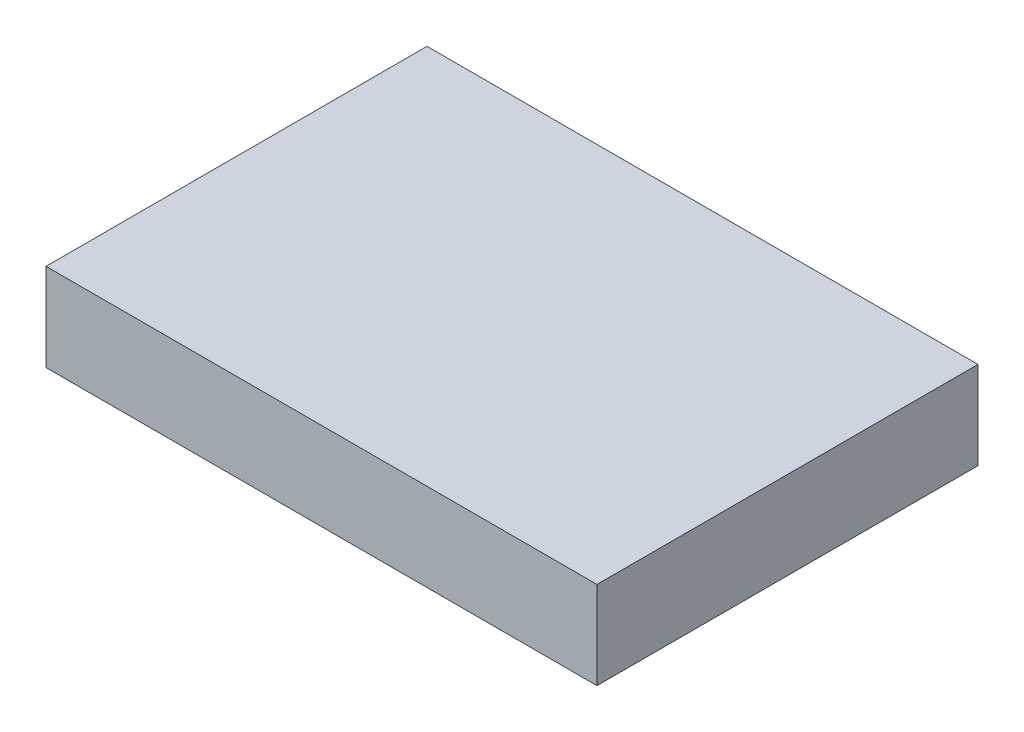
SolidWorks part; units mm, degrees
ref_plane "Front Plane" through (0, 0, 0) normal (0, 0, 1) x (1, 0, 0)
ref_plane "Top Plane" through (0, 0, 0) normal (0, 1, 0) x (1, 0, 0)
ref_plane "Right Plane" through (0, 0, 0) normal (1, 0, 0) x (0, 0, -1)
sketch "Sketch1" plane through (0, 0, 0) normal (0, 1, 0) x (1, 0, 0)
  line L0 (29.7205, 0) -> (-8.7318, 0) construction
  line L1 (-7.1155, 7.7492) -> (-7.1155, -5.9033) construction
  line L2 (-4.5755, 7.7492) -> (-4.5755, -5.9033) construction
  line L3 (118.7326, 278.2433) -> (634.0659, 278.2433) construction
  line L4 (24.9506, -7.4544) -> (24.9506, 3.6321) construction
  line L5 (22.4106, 3.6321) -> (22.4106, -6.4304) construction
  line L6 (-0.3815, -8.3015) -> (-0.3815, 5.7067) construction
  line L7 (17.6185, -7.7982) -> (17.6185, 5.0775) construction
  line L9 (4.1552, 14.4276) -> (10.4387, 14.4276)
  line L10 (4.1552, 14.4276) -> (4.1552, 10.082)
  line L11 (4.1552, 10.082) -> (10.4387, 10.082)
  line L12 (10.4387, 14.4276) -> (10.4387, 10.082)
  dimension "D1" = 2.54
  dimension "D2" = 2.54
  dimension "D3" = 32.0661
  dimension "D4" = 18
extrude "Boss-Extrude1" add sketch "Sketch1" along normal blind 1
